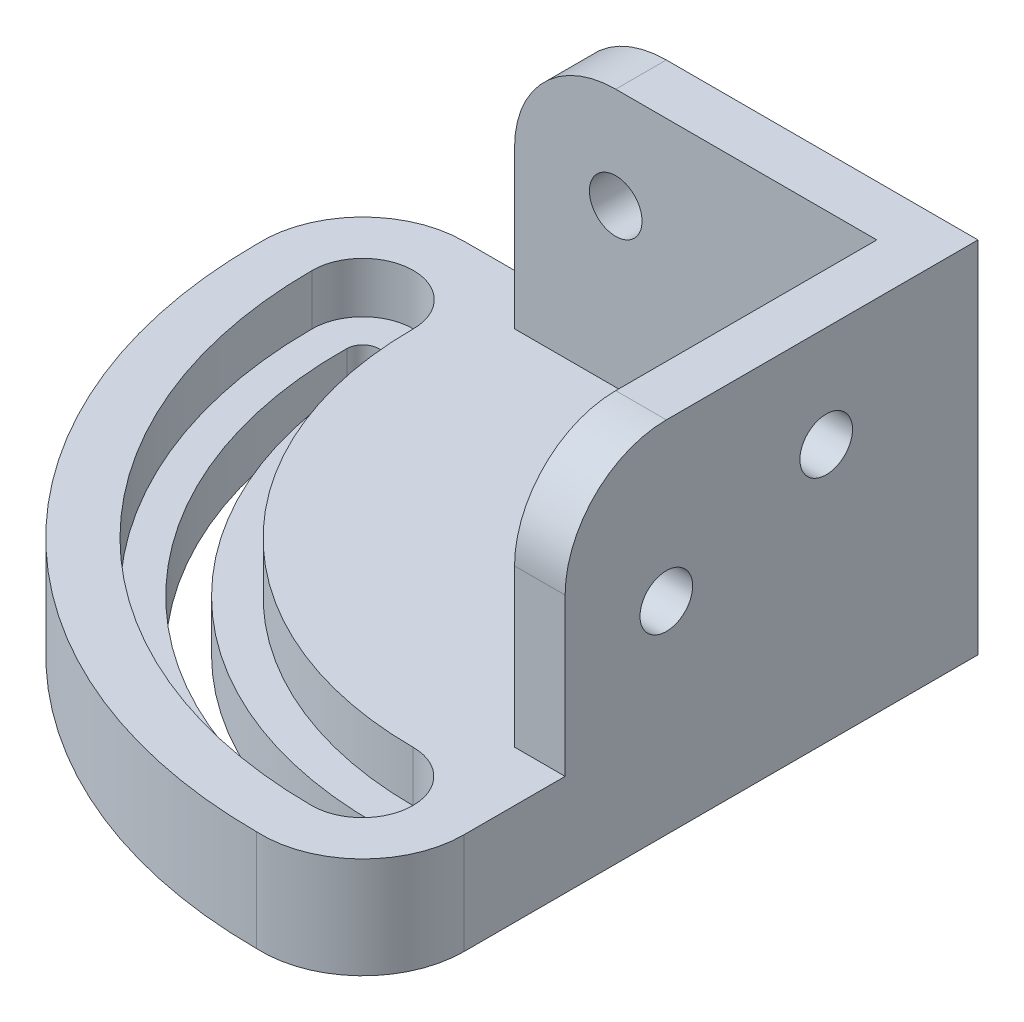
SolidWorks part; units mm, degrees
ref_plane "Front Plane" through (0, 0, 0) normal (0, 0, 1) x (1, 0, 0)
ref_plane "Top Plane" through (0, 0, 0) normal (0, 1, 0) x (1, 0, 0)
ref_plane "Right Plane" through (0, 0, 0) normal (1, 0, 0) x (0, 0, -1)
sketch "Sketch1" plane through (0, 0, 0) normal (0, 1, 0) x (1, 0, 0)
  line L5 (25.4, -25.4) -> (15.4, -25.4) construction
  line L9 (-25.4, 25.4) -> (25.4, 25.4)
  line L10 (25.4, -25.4) -> (25.4, 25.4)
  line L11 (-25.4, -25.4) -> (25.4, 25.4) construction
  line L12 (-25.4, 25.4) -> (25.4, -25.4) construction
  line L13 (14.8825, -35.3866) -> (14.8825, 14.8825) construction
  line L14 (-25.4, 25.4) -> (-25.4, 15.4) construction
  line L16 (14.8825, 14.8825) -> (-36.7593, 14.8825) construction
  arc A4 (25.4, -25.4) -> (14.8825, -35.3866) centre (15.4, -25.4) cw
  arc A9 (14.8825, -35.3866) -> (-35.3866, 14.8825) centre (14.8825, 14.8825) cw
  arc A10 (-35.3866, 14.8825) -> (-25.4, 25.4) centre (-25.4, 15.4) cw
  arc A11 (15.4, -25.4) -> (-25.4, 15.4) centre (14.8825, 14.8825) cw construction
  arc A12 (-26.9999, 15.4206) -> (15.4206, -26.9999) centre (14.8825, 14.8825) ccw
  arc A13 (-23.8001, 15.3794) -> (15.3794, -23.8001) centre (14.8825, 14.8825) ccw
  arc A14 (-23.8001, 15.3794) -> (-26.9999, 15.4206) centre (-25.4, 15.4) ccw
  arc A15 (15.4206, -26.9999) -> (15.3794, -23.8001) centre (15.4, -25.4) ccw
  point P0 (0, 0)
  point P1 (0, 0)
  point P14 (-13.6039, -13.6039)
  dimension "D1" = 50.8
  dimension "D2" = 10
extrude "Boss-Extrude1" add sketch "Sketch1" along normal blind 10
sketch "Sketch3" plane through (0, 10, 0) normal (0, 1, 0) x (1, 0, 0)
  line L0 (-23.8001, 15.3794) -> (15.4, 15.3794) construction
  line L4 (15.4, -23.8) -> (15.4, 15.3794) construction
  arc A1 (15.4206, -26.9999) -> (15.3794, -23.8001) centre (15.4, -25.4) ccw construction
  arc A2 (-25.4, 15.4) -> (15.3794, -25.4206) centre (15.4, 15.3794) ccw construction
  arc A3 (-30.4, 15.4025) -> (15.3769, -30.4206) centre (15.4, 15.3794) ccw
  arc A4 (-20.4, 15.3975) -> (15.382, -20.4206) centre (15.4, 15.3794) ccw
  arc A5 (-20.4, 15.3975) -> (-30.4, 15.4025) centre (-25.4, 15.4) ccw
  arc A6 (15.3769, -30.4206) -> (15.382, -20.4206) centre (15.3794, -25.4206) ccw
  point P3 (-13.4645, -13.456)
extrude "Cut-Extrude1" cut sketch "Sketch3" against normal blind 5
sketch "Sketch4" plane through (25.4, 0, 0) normal (1, 0, 0) x (0, 0, -1)
  line L0 (-15.4, 10) -> (-15.4, 35.5093) construction
  line L1 (-15.4, 25.5093) -> (-15.4, 0)
  line L2 (-25.4, 10) -> (25.4, 10) construction
  line L7 (-25.4, 0) -> (25.4, 0) construction
  line L8 (-5.4, 35.5093) -> (25.4, 35.5093)
  line L12 (-15.4, 0) -> (25.4, 0)
  line L13 (25.4, 0) -> (25.4, 35.5093)
  line L14 (25.4, 25.5093) -> (10.4, 25.5093) construction
  line L15 (10.4, 25.5093) -> (10.4, 35.5093) construction
  line L16 (-15.4, 20) -> (-5.4, 20) construction
  line L17 (-5.4, 20) -> (-5.4, 10) construction
  arc A3 (-5.4, 35.5093) -> (-15.4, 25.5093) centre (-5.4, 25.5093) ccw
  circle A5 centre (10.4, 25.5093) radius 2.6
  circle A6 centre (-5.4, 20) radius 2.6
  dimension "D2" = 10
  dimension "D1" = 10
  dimension "D3" = 10
extrude "Boss-Extrude2" add sketch "Sketch4" against normal blind 5
sketch "Sketch5" plane through (0, 0, -25.4) normal (0, 0, -1) x (-1, 0, 0)
  line L0 (15.4, 10) -> (15.4, 35.5093) construction
  line L1 (-20.4, 10) -> (25.4, 10) construction
  line L2 (-20.4, 20) -> (-10.4, 20) construction
  line L3 (5.4, 35.5093) -> (-25.4, 35.5093)
  line L7 (-20.4, 10) -> (-20.4, 35.5093) construction
  line L8 (-25.4, 35.5093) -> (-25.4, 0)
  line L9 (-25.4, 0) -> (15.4, 0)
  line L10 (-25.4, 0) -> (25.4, 0) construction
  line L11 (15.4, 0) -> (15.4, 25.5093)
  line L12 (-10.4, 20) -> (-10.4, 10) construction
  arc A1 (5.4, 35.5093) -> (15.4, 25.5093) centre (5.4, 25.5093) cw
  circle A2 centre (5.4, 25.5093) radius 2.6
  circle A3 centre (-10.4, 20) radius 2.6
  dimension "D2" = 10
  dimension "D1" = 10
extrude "Boss-Extrude3" add sketch "Sketch5" against normal blind 5
